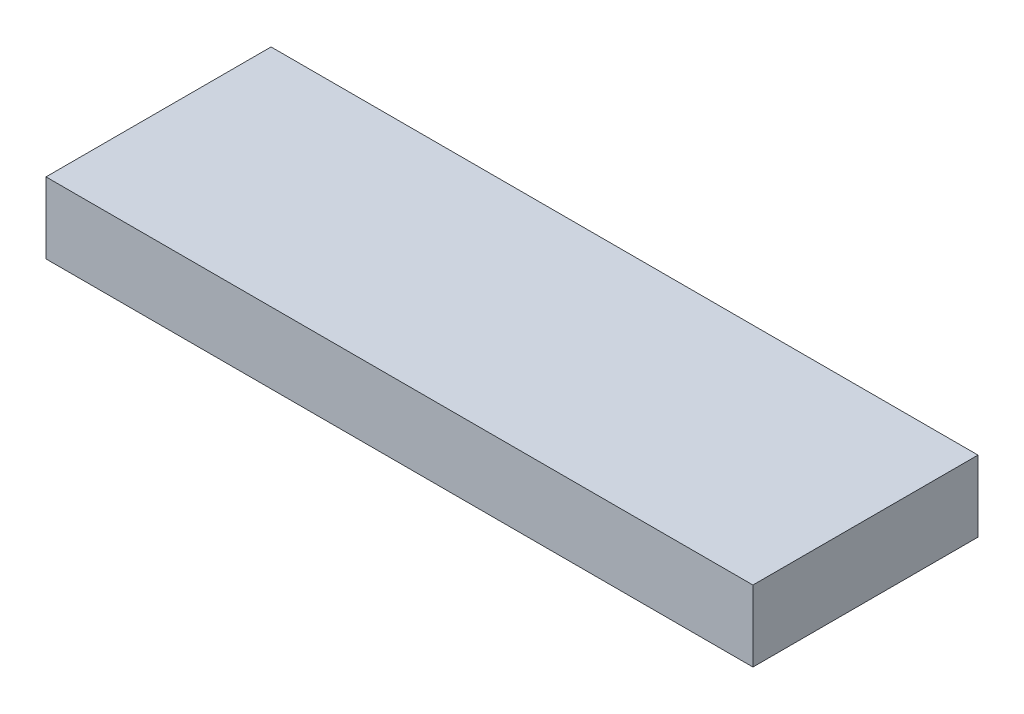
SolidWorks part; units mm, degrees
material "MDF"
ref_plane "Front Plane" through (0, 0, 0) normal (0, 0, 1) x (1, 0, 0)
ref_plane "Top Plane" through (0, 0, 0) normal (0, 1, 0) x (1, 0, 0)
ref_plane "Right Plane" through (0, 0, 0) normal (1, 0, 0) x (0, 0, -1)
sketch "Sketch1" plane through (0, 0, 0) normal (0, 0, 1) x (1, 0, 0)
  line L0 (-94.7388, -19.05) -> (-94.7388, -298.45) construction
  line L1 (-94.7388, -282.575) -> (94.7388, -282.575)
  line L2 (-94.7388, -282.575) -> (-94.7388, -263.525)
  line L3 (-94.7388, -263.525) -> (94.7388, -263.525)
  line L4 (94.7388, -282.575) -> (94.7388, -263.525)
  line L5 (94.7388, -19.05) -> (94.7388, -298.45) construction
  dimension "D1" = 19.05
  dimension "D2" = 3.175
extrude "Boss-Extrude1" add sketch "Sketch1" along normal up to surface (60.325 mm away)
hole_wizard "Hole1" positions "Sketch2" profile "Sketch3" legacy
sketch "Sketch2" plane through (0, 3.175, -25.4) normal (0, 0, -1) x (-1, 0, 0)
  line L0 (218.5638, 0) -> (218.5638, -437.642) construction
  line L4 (104.2638, 0) -> (104.2638, -298.45) construction
  line L13 (120.1388, -460.375) -> (120.1388, -311.15) construction
  line L16 (126.4888, -311.15) -> (113.7888, -311.15) construction
  line L18 (126.4888, -304.8) -> (-126.4888, -304.8) construction
  line L22 (94.7388, -276.225) -> (-94.7388, -276.225) construction
  line L24 (-94.7388, -285.75) -> (-94.7388, -266.7) construction
  line L26 (94.7388, -285.75) -> (94.7388, -266.7) construction
  line L27 (-94.7388, 0) -> (-94.7388, -19.05) construction
  line L29 (94.7388, 0) -> (94.7388, -19.05) construction
  line L31 (94.7388, -9.525) -> (-94.7388, -9.525) construction
  point P15 (218.5638, -31.75)
  point P17 (218.5638, -218.821)
  point P19 (218.5638, -418.592)
  point P28 (104.2638, -19.05)
  point P30 (104.2638, -149.225)
  point P32 (104.2638, -279.4)
  point P69 (120.1388, -330.2)
  point P71 (120.1388, -441.325)
  point P76 (-120.1388, -441.325)
  point P77 (-120.1388, -330.2)
  point P80 (-104.2638, -279.4)
  point P81 (-104.2638, -149.225)
  point P82 (-104.2638, -19.05)
  point P83 (-218.5638, -418.592)
  point P84 (-218.5638, -218.821)
  point P85 (-218.5638, -31.75)
  point P99 (0, -304.8)
  point P101 (107.4388, -304.8)
  point P103 (-107.4388, -304.8)
  point P127 (75.6888, -276.225)
  point P129 (0, -276.225)
  point P131 (-75.6888, -276.225)
  point P152 (75.6888, -9.525)
  point P154 (0, -9.525)
  point P156 (-75.6888, -9.525)
sketch "Sketch3" plane through (75.6888, -6.35, -25.4) normal (1, 0, 0) x (0, 1, 0)
  line L0 (0, 0) -> (0, 39.0539)
  line L1 (0, 39.0539) -> (1.5875, 38.1)
  line L2 (1.5875, 38.1) -> (1.5875, 4.0177)
  line L3 (1.5875, 4.0177) -> (5.08, 0)
  line L4 (5.08, 0) -> (0, 0)
  line L5 (0, -14.3089) -> (0, 102.4216) construction
  line L6 (0, 39.0539) -> (-1.5875, 38.1) construction
  line L7 (-1.5875, 4.0177) -> (-5.08, 0) construction
  dimension "Diameter" = 3.175
  dimension "Depth" = 38.1
  dimension "C-Sink Diameter" = 10.16
  dimension "C-Sink Angle" = 82
  dimension "Drill Angle" = 118
